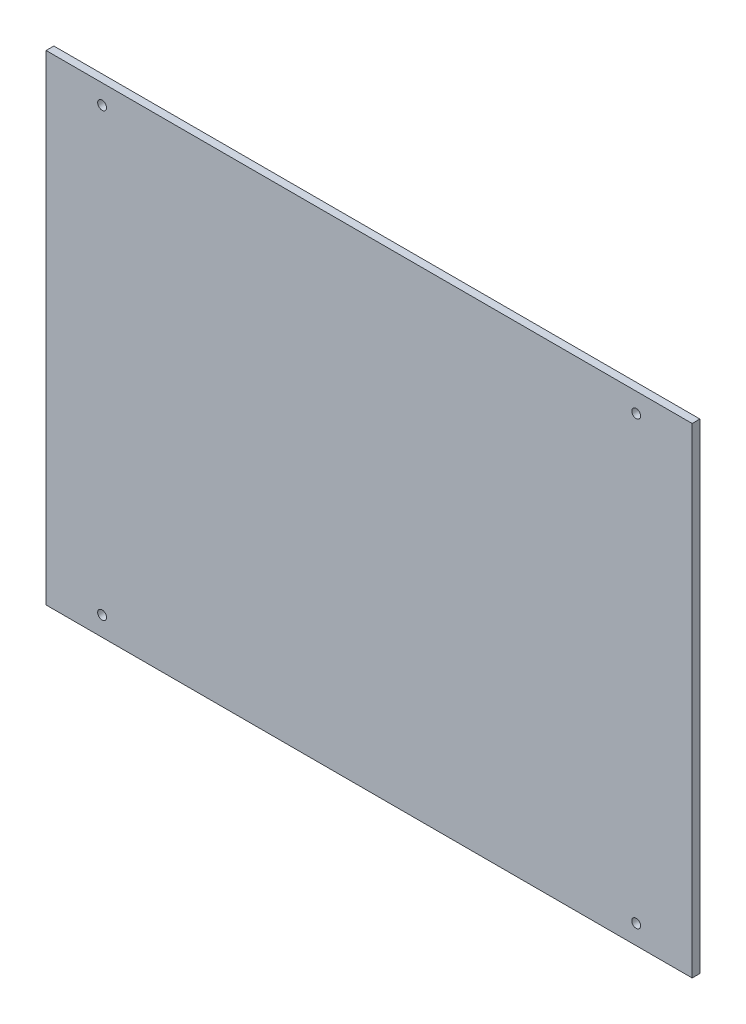
SolidWorks part; units mm, degrees
ref_plane "Plan de face" through (0, 0, 0) normal (0, 0, 1) x (1, 0, 0)
ref_plane "Plan de dessus" through (0, 0, 0) normal (0, 1, 0) x (1, 0, 0)
ref_plane "Plan de droite" through (0, 0, 0) normal (1, 0, 0) x (0, 0, -1)
sketch "Esquisse1" plane through (0, 0, 0) normal (0, 0, 1) x (1, 0, 0)
  line L0 (0, 143.6349) -> (0, -151.1597) construction
  line L1 (150, 112.5) -> (-150, 112.5) construction
  line L2 (150, 112.5) -> (150, -112.5) construction
  line L3 (150, -112.5) -> (-150, -112.5) construction
  line L4 (-150, 112.5) -> (-150, -112.5) construction
  line L5 (150, 112.5) -> (-150, -112.5) construction
  line L6 (150, -112.5) -> (-150, 112.5) construction
  line L7 (-305.4178, 0) -> (251.4164, 0) construction
  line L9 (150, -111.5) -> (-150, -111.5)
  line L10 (150, -111.5) -> (150, 111.5)
  line L11 (150, 111.5) -> (-150, 111.5)
  line L12 (-150, -111.5) -> (-150, 111.5)
  line L13 (150, -111.5) -> (-150, 111.5) construction
  line L14 (150, 111.5) -> (-150, -111.5) construction
  circle A0 centre (-124, 102.5) radius 2.05
  circle A1 centre (-124, -102.5) radius 2.05
  circle A2 centre (124, -102.5) radius 2.05
  circle A3 centre (124, 102.5) radius 2.05
  point P0 (0, 0)
  point P18 (0, 0)
  point P23 (-125, 102.5)
  dimension "D2" = 4.1
  dimension "D1" = 225
  dimension "D3" = 300
  dimension "D4" = 124
  dimension "D5" = 102.5
  dimension "D6" = 223
  dimension "D7" = 300
extrude "Boss.-Extru.1" add sketch "Esquisse1" against normal blind 3.6
